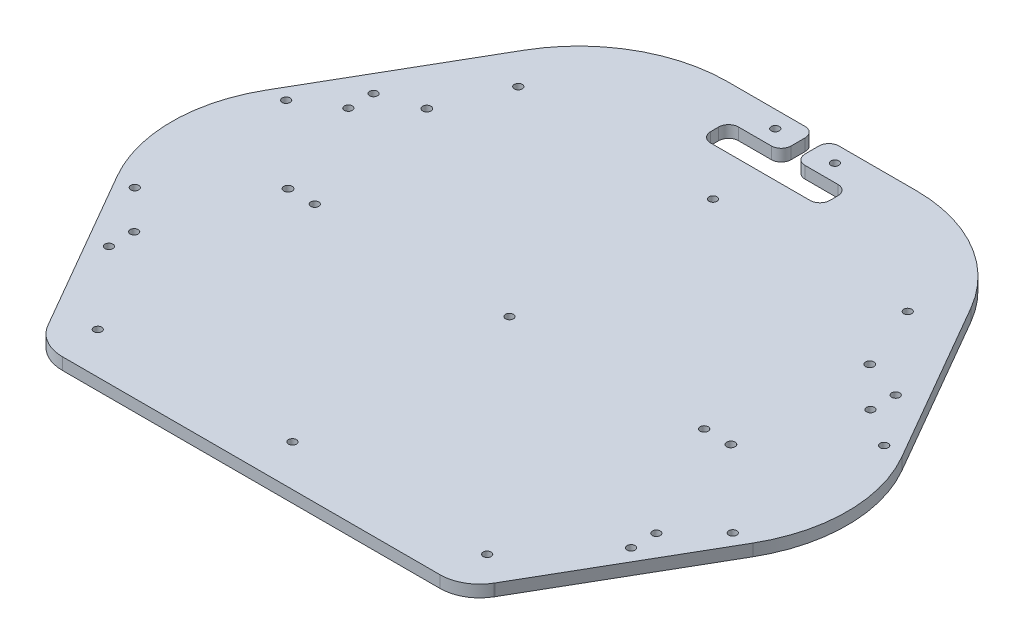
SolidWorks part; units mm, degrees
ref_plane "Plano frontal" through (0, 0, 0) normal (0, 0, 1) x (1, 0, 0)
ref_plane "Plano superior" through (0, 0, 0) normal (0, 1, 0) x (1, 0, 0)
ref_plane "Plano direito" through (0, 0, 0) normal (1, 0, 0) x (0, 0, -1)
ref_plane "Plano1" through (0, 6, 0) normal (0, 1, 0) x (1, 0, 0)
sketch "Esboço1" plane through (0, 6, 0) normal (0, 1, 0) x (1, 0, 0)
  line L0 (-94.9993, -130) -> (94.9993, -130)
  line L1 (112.4519, -119.7724) -> (159.9519, -37.5)
  line L2 (159.9519, 37.5) -> (112.4519, 119.7724)
  line L3 (47.5, 157.2724) -> (8.5, 157.2724)
  line L4 (3.5, 152.2724) -> (3.5, 145.2724)
  line L5 (8.5, 140.2724) -> (25, 140.2724)
  line L6 (30, 135.2724) -> (30, 131.2724)
  line L7 (25, 126.2724) -> (-25, 126.2724)
  line L8 (-30, 131.2724) -> (-30, 135.2724)
  line L9 (-25, 140.2724) -> (-8.5, 140.2724)
  line L10 (-3.5, 145.2724) -> (-3.5, 152.2724)
  line L11 (-8.5, 157.2724) -> (-47.5, 157.2724)
  line L12 (-112.4519, 119.7724) -> (-159.9519, 37.5)
  line L13 (-159.9519, -37.5) -> (-112.4519, -119.7724)
  circle A0 centre (150.5, -38.1) radius 2
  circle A1 centre (150.5, 38.1) radius 2
  circle A2 centre (-150.5, -38.1) radius 2
  circle A3 centre (-150.5, 38.1) radius 2
  circle A4 centre (15, 148.77) radius 2
  circle A5 centre (-15, 148.77) radius 2
  circle A6 centre (131.4, -57.5) radius 2
  circle A7 centre (-131.4, -57.5) radius 2
  circle A8 centre (131.4, 63) radius 2
  circle A9 centre (-131.4, 63) radius 2
  circle A10 centre (131.4, -70.2) radius 2
  circle A11 centre (-131.4, -70.2) radius 2
  circle A12 centre (131.4, 50.3) radius 2
  circle A13 centre (-131.4, 50.3) radius 2
  circle A14 centre (98, -109.22) radius 2
  circle A15 centre (111.4552, 0) radius 2.1
  circle A16 centre (111.4552, 69.85) radius 2.1
  circle A17 centre (-111.4552, 0) radius 2.1
  circle A18 centre (-111.4552, 69.85) radius 2.1
  circle A19 centre (-97.9932, 0) radius 2
  circle A20 centre (97.9932, 0) radius 2
  circle A21 centre (0, 0) radius 2
  circle A22 centre (0, -109.22) radius 2
  circle A23 centre (0, 102.4382) radius 2
  circle A24 centre (-98, 102.4382) radius 2
  circle A25 centre (98, 102.4382) radius 2
  circle A26 centre (-98, -109.22) radius 2
  arc A27 (-112.2717, -120.0828) -> (-94.9993, -130) centre (-94.9993, -110) ccw
  arc A28 (94.9993, -130) -> (112.2717, -120.0828) centre (94.9993, -110) ccw
  arc A29 (112.2717, -120.0828) -> (112.4519, -119.7724) centre (47.5, -82.2724) ccw
  arc A30 (159.9519, -37.5) -> (159.9519, 37.5) centre (95, 0) ccw
  arc A31 (112.4519, 119.7724) -> (47.5, 157.2724) centre (47.5, 82.2724) ccw
  arc A32 (8.5, 157.2724) -> (3.5, 152.2724) centre (8.5, 152.2724) ccw
  arc A33 (3.5, 145.2724) -> (8.5, 140.2724) centre (8.5, 145.2724) ccw
  arc A34 (25, 140.2724) -> (30, 135.2724) centre (25, 135.2724) cw
  arc A35 (30, 131.2724) -> (25, 126.2724) centre (25, 131.2724) cw
  arc A36 (-25, 126.2724) -> (-30, 131.2724) centre (-25, 131.2724) cw
  arc A37 (-30, 135.2724) -> (-25, 140.2724) centre (-25, 135.2724) cw
  arc A38 (-8.5, 140.2724) -> (-3.5, 145.2724) centre (-8.5, 145.2724) ccw
  arc A39 (-3.5, 152.2724) -> (-8.5, 157.2724) centre (-8.5, 152.2724) ccw
  arc A40 (-47.5, 157.2724) -> (-112.4519, 119.7724) centre (-47.5, 82.2724) ccw
  arc A41 (-159.9519, 37.5) -> (-159.9519, -37.5) centre (-95, 0) ccw
  arc A42 (-112.4519, -119.7724) -> (-112.2717, -120.0828) centre (-47.5, -82.2724) ccw
extrude "Ressalto-extrusão1" add sketch "Esboço1" against normal blind 6
